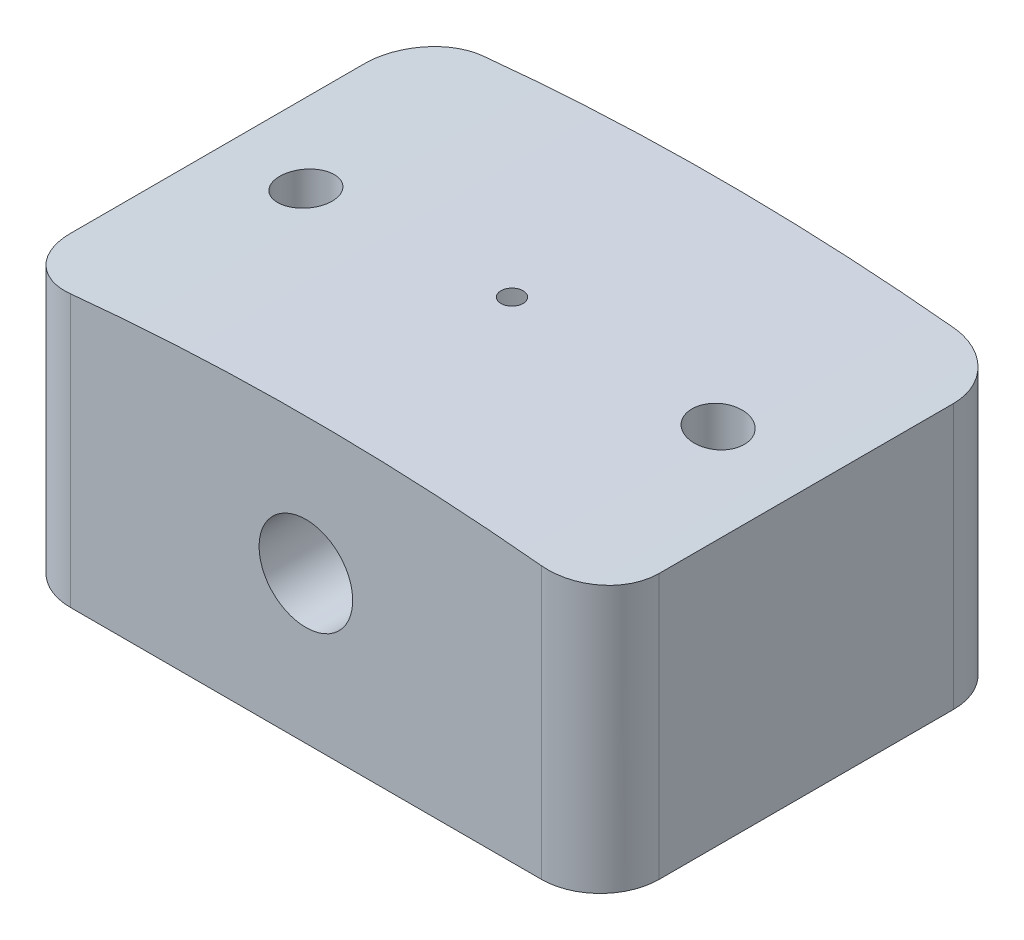
SolidWorks part; units mm, degrees
ref_plane "Front Plane" through (0, 0, 0) normal (0, 0, 1) x (1, 0, 0)
ref_plane "Top Plane" through (0, 0, 0) normal (0, 1, 0) x (1, 0, 0)
ref_plane "Right Plane" through (0, 0, 0) normal (1, 0, 0) x (0, 0, -1)
sketch "Sketch1" plane through (0, 0, 0) normal (0, 0, 1) x (1, 0, 0)
  line L2 (-12.6987, 100.8033) -> (-12.6987, 89.3733)
  line L3 (-12.6987, 89.3733) -> (12.6987, 89.3733)
  line L4 (12.6987, 89.3733) -> (12.6987, 100.8033)
  arc A1 (-12.6987, 100.8033) -> (12.6987, 100.8033) centre (0, 0) cw
extrude "Boss-Extrude1" add sketch "Sketch1" along normal blind 8.89 and the other way blind 8.89
sketch "Sketch2" plane through (0, 89.3733, 0) normal (0, -1, 0) x (1, 0, 0)
  circle A0 centre (0, 0) radius 4.7625
hole_wizard "3/8 (0.375) Diameter Slot1" positions "Sketch4" profile "Sketch5" size "3/8" standard "ANSI Inch" slot yes
sketch "Sketch4" plane through (0, 89.3733, 0) normal (0, -1, 0) x (-1, 0, 0)
  point P0 (0, 0)
sketch "Sketch5" plane through (0, 89.3733, 0) normal (1, 0, 0) x (0, 0, -1)
  line L0 (0, 0) -> (0, 12.5136)
  line L1 (0, 12.5136) -> (4.7625, 9.652)
  line L2 (4.7625, 9.652) -> (4.7625, 0)
  line L5 (4.7625, 0) -> (0, 0)
  line L10 (0, 12.5136) -> (-4.7625, 9.652) construction
  line L11 (0, -6.35) -> (0, 107.95) construction
  dimension "Hole Dia." = 9.525
  dimension "Hole Depth" = 9.652
  dimension "Drill Angle" = 118
sketch "Sketch6" plane through (0, 89.3733, 0) normal (0, -1, 0) x (1, 0, 0)
  line L0 (12.6987, -8.89) -> (12.6987, 8.89) construction
  line L1 (-12.6987, -8.89) -> (-12.6987, 8.89) construction
  circle A0 centre (8.8887, 0) radius 1.4224
  circle A1 centre (-8.8887, 0) radius 1.4224
  dimension "D1" = 3.81
  dimension "D2" = 3.81
hole_wizard "Tap Drill for #4-40 Tap1" positions "Sketch8" profile "Sketch9" hole size "#4-40" standard "ANSI Inch" end condition through all
sketch "Sketch8" plane through (0, 89.3733, 0) normal (0, -1, 0) x (-1, 0, 0)
  point P0 (-8.8887, 0)
  point P3 (8.8887, 0)
sketch "Sketch9" plane through (8.8887, 89.3733, 0) normal (1, 0, 0) x (0, 0, -1)
  line L0 (0, 0) -> (0, 12.2267)
  line L1 (0, 12.2267) -> (1.1303, 12.2267)
  line L2 (1.1303, 12.2267) -> (1.1303, 0)
  line L5 (1.1303, 0) -> (0, 0)
  line L11 (0, -6.35) -> (0, 107.95) construction
  dimension "Thru Hole Dia." = 2.2606
  dimension "Thru Hole Depth" = 12.2267
fillet "Fillet1" radius 2.54 4 edges at (12.6987, 95.0883, 8.89) (12.6987, 95.0883, -8.89) (-12.6987, 95.0883, -8.89) (-12.6987, 95.0883, 8.89)
sketch "Sketch10" plane through (0, 0, -8.89) normal (0, 0, -1) x (-1, 0, 0)
  line L0 (10.1587, 89.3733) -> (-10.1587, 89.3733) construction
  point P0 (0, 95.7233)
  dimension "D1" = 6.35
hole_wizard "#10-32 Tapped Hole1" positions "Sketch12" profile "Sketch11" tap size "#10-32" standard "ANSI Inch" end condition through all
sketch "Sketch12" plane through (0, 0, -8.89) normal (0, 0, -1) x (-1, 0, 0)
  point P0 (0, 95.7233)
sketch "Sketch11" plane through (0, 95.7233, -8.89) normal (1, 0, 0) x (0, 1, 0)
  line L0 (0, 0) -> (0, 17.78)
  line L1 (0, 17.78) -> (2.0193, 17.78)
  line L2 (2.0193, 17.78) -> (2.0193, 0)
  line L5 (2.0193, 0) -> (0, 0)
  line L11 (0, -6.35) -> (0, 107.95) construction
  dimension "Thread Major Dia." = 4.0386
  dimension "Thru Tap Drill Depth" = 17.78
